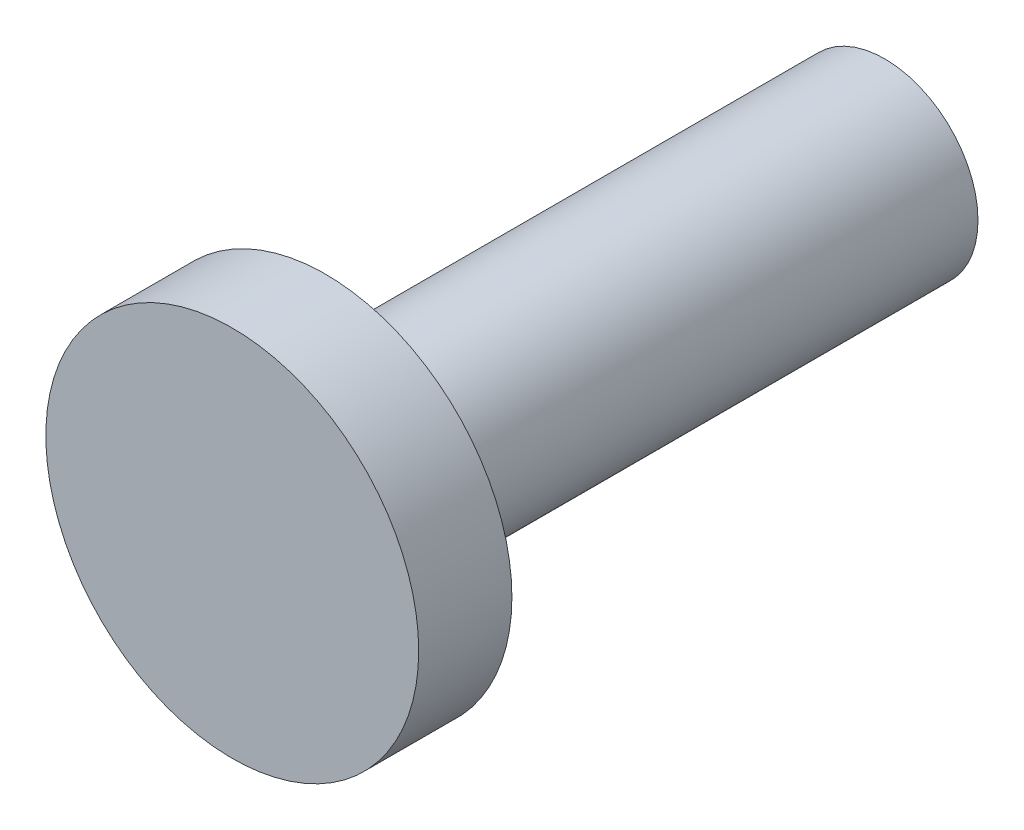
SolidWorks part; units mm, degrees
ref_plane "정면" through (0, 0, 0) normal (0, 0, 1) x (1, 0, 0)
ref_plane "윗면" through (0, 0, 0) normal (0, 1, 0) x (1, 0, 0)
ref_plane "우측면" through (0, 0, 0) normal (1, 0, 0) x (0, 0, -1)
sketch "스케치1" plane through (0, 0, 0) normal (0, 0, 1) x (1, 0, 0)
  circle A0 centre (0, 0) radius 10
  dimension "D1" = 20
extrude "보스-돌출1" add sketch "스케치1" along normal blind 60
sketch "스케치2" plane through (0, 0, 60) normal (0, 0, 1) x (1, 0, 0)
  circle A0 centre (0, 0) radius 20
  dimension "D1" = 40
extrude "보스-돌출2" add sketch "스케치2" along normal blind 10
